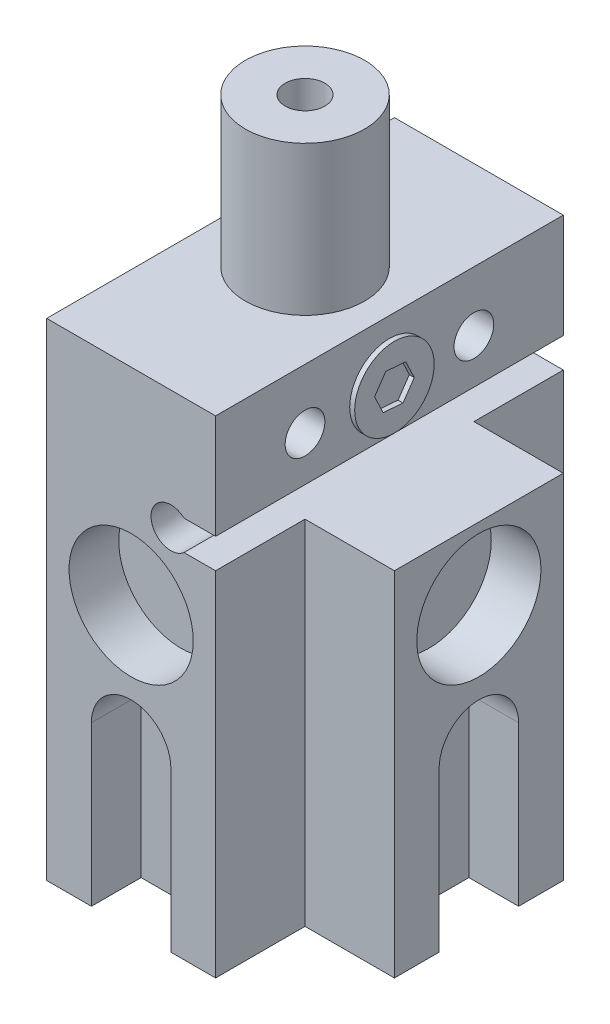
SolidWorks part; units mm, degrees
material "1060 Alloy"
ref_plane "Front Plane" through (0, 0, 0) normal (0, 0, 1) x (1, 0, 0)
ref_plane "Top Plane" through (0, 0, 0) normal (0, 1, 0) x (1, 0, 0)
ref_plane "Right Plane" through (0, 0, 0) normal (1, 0, 0) x (0, 0, -1)
sketch "Sketch1" plane through (0, 0, 0) normal (1, 0, 0) x (0, 0, -1)
  line L1 (0, 0) -> (35, 0)
  line L2 (0, 0) -> (0, 49)
  line L3 (0, 49) -> (35, 49)
  line L4 (35, 0) -> (35, 49)
  dimension "D1" = 35
  dimension "D2" = 49
extrude "Boss-Extrude1" add sketch "Sketch1" along normal blind 17
sketch "Sketch2" plane through (17, 0, 0) normal (1, 0, 0) x (0, 0, -1)
  line L0 (35, 43) -> (26, 43) construction
  line L1 (35, 0) -> (35, 49) construction
  line L2 (26, 43) -> (26, 49) construction
  line L3 (35, 49) -> (0, 49) construction
  line L4 (0, 43) -> (9, 43) construction
  line L5 (0, 49) -> (0, 0) construction
  line L6 (9, 43) -> (9, 49) construction
  circle A0 centre (9, 43) radius 2
  circle A1 centre (26, 43) radius 2
  dimension "D4" = 4
  dimension "D5" = 4
  dimension "D1" = 9
  dimension "D2" = 6
  dimension "D3" = 9
extrude "Cut-Extrude1" cut sketch "Sketch2" against normal blind 37
sketch "Sketch3" plane through (17, 0, 0) normal (1, 0, 0) x (0, 0, -1)
  line L0 (0, 0) -> (35, 0) construction
  line L1 (26, 0) -> (9, 0)
  line L2 (26, 0) -> (26, 35.5)
  line L3 (26, 35.5) -> (9, 35.5)
  line L4 (9, 0) -> (9, 35.5)
  line L5 (35, 0) -> (35, 49) construction
  dimension "D1" = 35.5
  dimension "D2" = 17
  dimension "D3" = 9
extrude "Boss-Extrude2" add sketch "Sketch3" along normal blind 9
sketch "Sketch4" plane through (0, 0, 0) normal (-1, 0, 0) x (0, 0, 1)
  line L0 (0, 0) -> (-35, 0) construction
  line L1 (-9, 0) -> (-26, 0)
  line L2 (-9, 0) -> (-9, 35.5)
  line L3 (-9, 35.5) -> (-26, 35.5)
  line L4 (-26, 0) -> (-26, 35.5)
  line L5 (-35, 0) -> (-35, 49) construction
  dimension "D1" = 17
  dimension "D2" = 9
  dimension "D3" = 35.5
extrude "Boss-Extrude3" add sketch "Sketch4" along normal blind 9
sketch "Sketch5" plane through (0, 0, 0) normal (0, 0, 1) x (1, 0, 0)
  line L0 (17, 49) -> (17, 0) construction
  line L1 (17, 35.5) -> (13.8229, 35.5)
  line L2 (17, 35.5) -> (17, 38.5)
  line L3 (17, 38.5) -> (13.8229, 38.5)
  line L5 (17, 0) -> (0, 0) construction
  arc A0 (13.8229, 38.5) -> (13.8229, 35.5) centre (12.5, 37) ccw
  dimension "D4" = 4
  dimension "D5" = 4.5
  dimension "D2" = 35.5
  dimension "D3" = 3
extrude "Cut-Extrude2" cut sketch "Sketch5" against normal blind 59
sketch "Sketch6" plane through (26, 0, 0) normal (1, 0, 0) x (0, 0, -1)
  line L0 (26, 35.5) -> (9, 35.5) construction
  line L1 (26, 0) -> (26, 35.5) construction
  circle A0 centre (17.5, 28.25) radius 6.25
  dimension "D1" = 12.5
  dimension "D2" = 7.25
  dimension "D3" = 8.5
extrude "Cut-Extrude3" cut sketch "Sketch6" against normal blind 5
sketch "Sketch7" plane through (-9, 0, 0) normal (-1, 0, 0) x (0, 0, 1)
  line L0 (-9, 0) -> (-9, 35.5) construction
  line L1 (-9, 35.5) -> (-26, 35.5) construction
  circle A0 centre (-17.5, 28.25) radius 6.25
  dimension "D1" = 12.5
  dimension "D2" = 8.5
  dimension "D3" = 7.25
extrude "Cut-Extrude4" cut sketch "Sketch7" against normal blind 5
sketch "Sketch8" plane through (0, 0, -35) normal (0, 0, -1) x (-1, 0, 0)
  line L0 (-13.8229, 35.5) -> (-17, 35.5) construction
  line L1 (0, 0) -> (0, 49) construction
  circle A0 centre (-8.5, 28.25) radius 6.25
  point P4 (-15.4114, 35.5)
  dimension "D1" = 12.5
  dimension "D2" = 7.25
  dimension "D3" = 8.5
extrude "Cut-Extrude5" cut sketch "Sketch8" against normal blind 5
sketch "Sketch9" plane through (0, 0, 0) normal (0, 0, 1) x (1, 0, 0)
  line L0 (13.8229, 35.5) -> (17, 35.5) construction
  line L1 (17, 35.5) -> (17, 0) construction
  circle A0 centre (8.5, 28.25) radius 6.25
  dimension "D1" = 12.5
  dimension "D2" = 7.25
  dimension "D3" = 8.5
extrude "Cut-Extrude6" cut sketch "Sketch9" against normal blind 5
sketch "Sketch10" plane through (17, 0, 0) normal (1, 0, 0) x (0, 0, -1)
  line L0 (9, 43) -> (26, 43) construction
  line L2 (18.6366, 44.6532) -> (16.6366, 44.8109)
  line L3 (16.6366, 44.8109) -> (15.5, 43.1577)
  line L4 (15.5, 43.1577) -> (16.3634, 41.3468)
  line L5 (16.3634, 41.3468) -> (18.3634, 41.1891)
  line L6 (18.3634, 41.1891) -> (19.5, 42.8423)
  line L7 (19.5, 42.8423) -> (18.6366, 44.6532)
  circle A1 centre (17.5, 43) radius 4
  circle A2 centre (17.5, 43) radius 1.7374 construction
  dimension "D1" = 8
  dimension "D2" = 4
extrude "Boss-Extrude4" add sketch "Sketch10" along normal blind 0.5
sketch "Sketch11" plane through (26, 0, 0) normal (1, 0, 0) x (0, 0, -1)
  line L0 (9, 0) -> (26, 0) construction
  line L1 (13.5, 0) -> (21.5, 0)
  line L2 (13.5, 0) -> (13.5, 16)
  line L4 (21.5, 0) -> (21.5, 16)
  line L5 (26, 0) -> (26, 35.5) construction
  arc A0 (21.5, 16) -> (13.5, 16) centre (17.5, 16) ccw
  dimension "D1" = 8
  dimension "D2" = 4.5
extrude "Cut-Extrude7" cut sketch "Sketch11" against normal blind 5
sketch "Sketch12" plane through (-9, 0, 0) normal (-1, 0, 0) x (0, 0, 1)
  line L0 (-26, 0) -> (-9, 0) construction
  line L1 (-21.5, 0) -> (-13.5, 0)
  line L2 (-21.5, 0) -> (-21.5, 16)
  line L4 (-13.5, 0) -> (-13.5, 16)
  line L5 (-9, 0) -> (-9, 35.5) construction
  arc A0 (-13.5, 16) -> (-21.5, 16) centre (-17.5, 16) ccw
  dimension "D1" = 4.5
  dimension "D2" = 8
  dimension "D3" = 16
extrude "Cut-Extrude8" cut sketch "Sketch12" against normal blind 5
sketch "Sketch13" plane through (0, 0, -35) normal (0, 0, -1) x (-1, 0, 0)
  line L0 (-17, 0) -> (0, 0) construction
  line L1 (-12.5, 0) -> (-4.5, 0)
  line L2 (-12.5, 0) -> (-12.5, 16)
  line L4 (-4.5, 0) -> (-4.5, 16)
  line L5 (0, 0) -> (0, 49) construction
  arc A0 (-4.5, 16) -> (-12.5, 16) centre (-8.5, 16) ccw
  dimension "D1" = 8
  dimension "D2" = 4.5
  dimension "D3" = 16
extrude "Cut-Extrude9" cut sketch "Sketch13" against normal blind 5
sketch "Sketch14" plane through (0, 0, 0) normal (0, 0, 1) x (1, 0, 0)
  line L0 (17, 0) -> (0, 0) construction
  line L1 (4.5, 0) -> (12.5, 0)
  line L2 (4.5, 0) -> (4.5, 16)
  line L4 (12.5, 0) -> (12.5, 16)
  line L5 (17, 35.5) -> (17, 0) construction
  arc A0 (12.5, 16) -> (4.5, 16) centre (8.5, 16) ccw
  dimension "D1" = 8
  dimension "D2" = 4.5
  dimension "D3" = 16
extrude "Cut-Extrude10" cut sketch "Sketch14" against normal blind 5
sketch "Sketch15" plane through (0, 49, 0) normal (0, 1, 0) x (1, 0, 0)
  line L0 (0, 35) -> (17, 0) construction
  circle A0 centre (8.5, 17.5) radius 6
  dimension "D1" = 12
extrude "Boss-Extrude5" add sketch "Sketch15" along normal blind 15
sketch "Sketch19" plane through (0, 64, 0) normal (0, 1, 0) x (1, 0, 0)
  circle A0 centre (8.5, 17.5) radius 2
  dimension "D1" = 4
extrude "Cut-Extrude11" cut sketch "Sketch19" against normal blind 24
